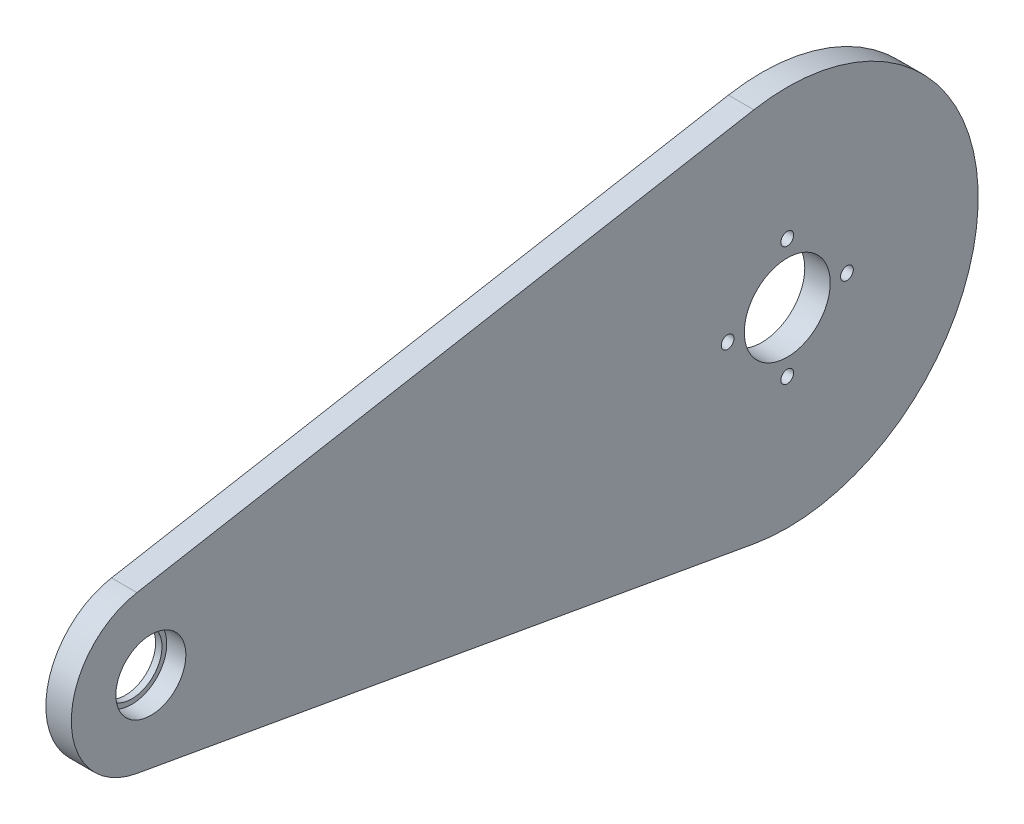
SolidWorks part; units mm, degrees
material "2024-T4"
ref_plane "Front Plane" through (0, 0, 0) normal (0, 0, 1) x (1, 0, 0)
ref_plane "Top Plane" through (0, 0, 0) normal (0, 1, 0) x (1, 0, 0)
ref_plane "Right Plane" through (0, 0, 0) normal (1, 0, 0) x (0, 0, -1)
sketch "Sketch1" plane through (0, 0, 0) normal (1, 0, 0) x (0, 0, -1)
  line L0 (0, 0) -> (-200, 0) construction
  line L1 (-204.375, 24.6142) -> (-10.5, 59.0741)
  line L2 (-204.375, -24.6142) -> (-10.5, -59.0741)
  circle A0 centre (0, 0) radius 13.5
  arc A1 (-10.5, -59.0741) -> (-10.5, 59.0741) centre (0, 0) ccw
  arc A2 (-204.375, 24.6142) -> (-204.375, -24.6142) centre (-200, 0) ccw
  circle A3 centre (-200, 0) radius 11
  dimension "D1" = 120
  dimension "D2" = 27
  dimension "D3" = 25
  dimension "D4" = 22
  dimension "D5" = 200
extrude "Boss-Extrude1" add sketch "Sketch1" along normal mid plane 8
sketch "Sketch2" plane through (4, 0, 0) normal (1, 0, 0) x (0, 0, -1)
  line L0 (0, 0) -> (0, 18.75) construction
  circle A0 centre (0, 18.75) radius 2
  circle A1 centre (18.75, 0) radius 2
  circle A2 centre (0, -18.75) radius 2
  circle A3 centre (-18.75, 0) radius 2
  point P13 (0, 0)
  dimension "D1" = 4
  dimension "D2" = 18.75
  dimension "D4" = 18.75
  dimension "D5" = 18.75
  dimension "D3" = 4
extrude "Cut-Extrude1" cut sketch "Sketch2" against normal through all
sketch "Sketch3" plane through (-4, 0, 0) normal (-1, 0, 0) x (0, 0, 1)
  circle A0 centre (200, 0) radius 9.5
  circle A1 centre (200, 0) radius 11 construction
  circle A2 centre (200, 0) radius 11
  dimension "D1" = 19
extrude "Boss-Extrude3" add sketch "Sketch3" against normal blind 2 contours A0
equation "\"D4@Sketch2\"=\"D2@Sketch2\""
equation "\"D5@Sketch2\"=\"D2@Sketch2\""
equation "\"shaft-diameter\"=20mm"
equation "\"key-length\"=12mm"
equation "\"key-width\"=4mm"
equation "\"flippershaft-wormgear-diameter\"= 35mm"
equation "\"shaft-ring-groove-depth\"=0.5mm"
equation "\"shaft-ring-groove-width\"= 1.3mm"
equation "\"mini-shaft-diameter\"= 12mm"
equation "\"mini-flipper-shaft-diameter\"= 26mm"
